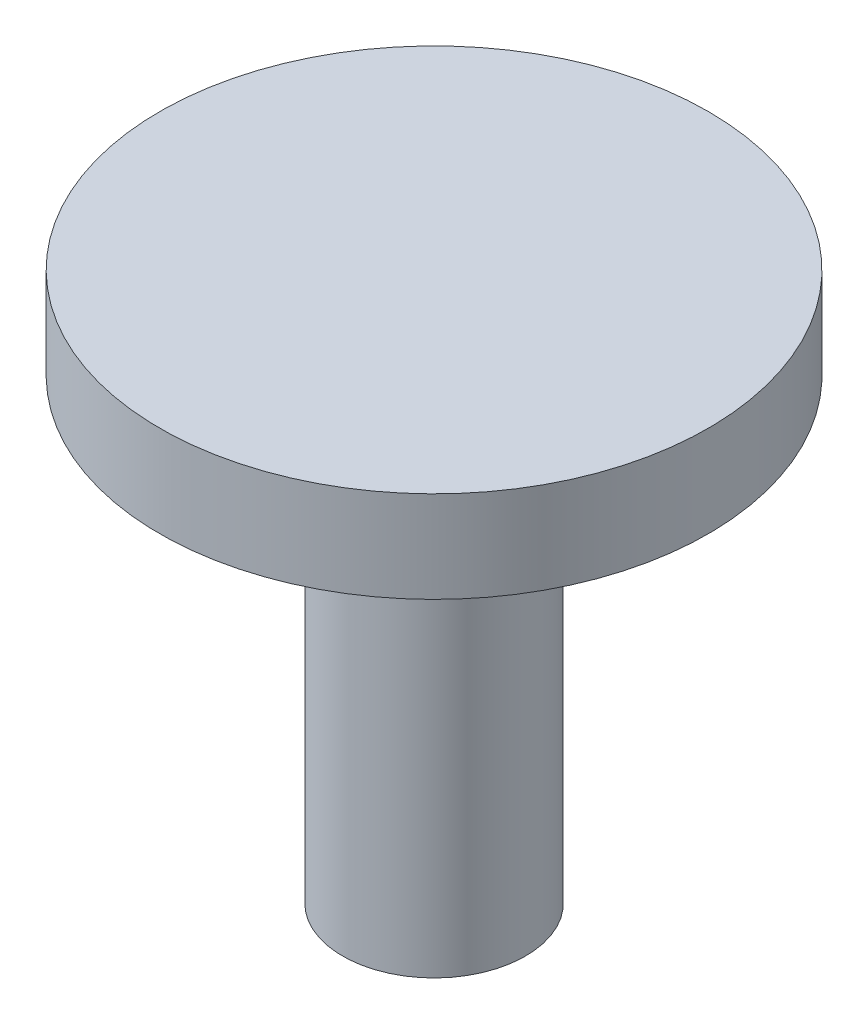
SolidWorks part; units mm, degrees
material "201 Annealed Stainless Steel (SS)"
ref_plane "Front Plane" through (0, 0, 0) normal (0, 0, 1) x (1, 0, 0)
ref_plane "Top Plane" through (0, 0, 0) normal (0, 1, 0) x (1, 0, 0)
ref_plane "Right Plane" through (0, 0, 0) normal (1, 0, 0) x (0, 0, -1)
sketch "Sketch1" plane through (0, 0, 0) normal (0, 0, 1) x (1, 0, 0)
  line L0 (0, 0) -> (0, 30)
  line L1 (0, 30) -> (15, 30)
  line L2 (15, 30) -> (15, 25)
  line L3 (5, 25) -> (5, 0)
  line L4 (5, 25) -> (15, 25)
  line L5 (5, 0) -> (0, 0)
revolve "Revolve1" add sketch "Sketch1" angle 360 about L0
